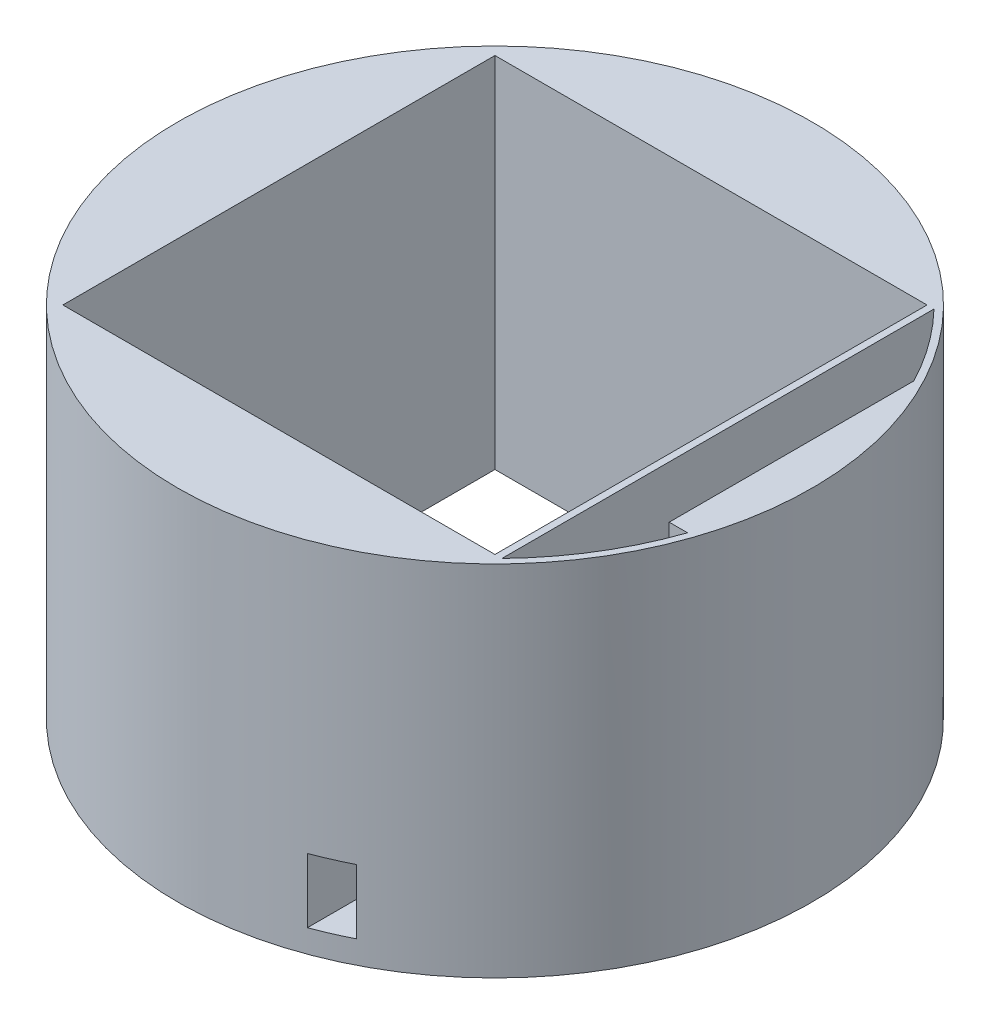
SolidWorks part; units mm, degrees
ref_plane "Front Plane" through (0, 0, 0) normal (0, 0, 1) x (1, 0, 0)
ref_plane "Top Plane" through (0, 0, 0) normal (0, 1, 0) x (1, 0, 0)
ref_plane "Right Plane" through (0, 0, 0) normal (1, 0, 0) x (0, 0, -1)
sketch "Sketch1" plane through (0, 0, 0) normal (0, 1, 0) x (1, 0, 0)
  line L0 (-23.5, -23.5) -> (-25.2587, -23.5)
  line L13 (-23.5, -23.5) -> (23.5, -23.5)
  line L14 (-23.5, -23.5) -> (-23.5, 23.5)
  line L15 (-23.5, 23.5) -> (23.5, 23.5)
  line L16 (23.5, -23.5) -> (23.5, 23.5)
  line L17 (-23.5, -23.5) -> (23.5, 23.5) construction
  line L18 (-23.5, 23.5) -> (23.5, -23.5) construction
  line L19 (-23.5, -10.9835) -> (-32.7049, -10.9835)
  line L20 (23.5, -23.5) -> (24.254, -23.5)
  line L21 (23.5, -10.9835) -> (31.9354, -10.9835)
  circle A3 centre (0, 0) radius 34.5
  arc A4 (24.254, -23.5) -> (31.9354, -10.9835) centre (0, 0) ccw
extrude "Boss-Extrude1" add sketch "Sketch1" along normal blind 2.5 contours A4 L20 L13 L19 A3 L0 L14 L15 L16 L21
sketch "Sketch2" plane through (0, 2.5, 0) normal (0, 1, 0) x (1, 0, 0)
  line L0 (23.5, -10.9835) -> (31.9354, -10.9835)
  line L1 (-23.5, -23.5) -> (11.9573, -23.5)
  line L2 (-23.5, -10.9835) -> (-23.5, 23.5)
  line L4 (23.5, -10.9835) -> (23.5, 23.5)
  line L5 (-23.5, -23.5) -> (23.5, 23.5) construction
  line L6 (-23.5, 23.5) -> (23.5, -23.5) construction
  line L7 (23.5, -23.5) -> (24.254, -23.5)
  line L8 (-23.5, -10.9835) -> (-32.7049, -10.9835)
  line L9 (-23.5, -23.5) -> (-25.2587, -23.5)
  line L10 (-25.2587, -23.5) -> (24.254, -23.5) construction
  line L14 (-23.5, 23.5) -> (23.5, 23.5)
  line L15 (15.6884, -23.5) -> (15.6884, -30.7266)
  line L16 (11.9573, -23.5) -> (11.9573, -32.3616)
  line L17 (15.6884, -23.5) -> (23.5, -23.5)
  arc A1 (24.254, -23.5) -> (31.9354, -10.9835) centre (0, 0) ccw
  arc A3 (15.6884, -30.7266) -> (11.9573, -32.3616) centre (0, 0) ccw
  arc M7 (31.9354, -10.9835) -> (24.254, -23.5) centre (0, 0) cw
  line M8 (24.254, -23.5) -> (-25.2587, -23.5)
  arc M9 (-25.2587, -23.5) -> (-32.7049, -10.9835) centre (0, 0) ccw
  line M10 (-32.7049, -10.9835) -> (-23.5, -10.9835)
  line M11 (-23.5, -10.9835) -> (-23.5, 23.5)
  line M12 (-23.5, 23.5) -> (23.5, 23.5)
  line M13 (23.5, 23.5) -> (23.5, -10.9835)
  line M14 (23.5, -10.9835) -> (31.9354, -10.9835)
extrude "Boss-Extrude2" add sketch "Sketch2" along normal blind 4.5 contours L15 M8 M9 M10 M11 M12 M13 M14 M7 | L16 M8 M9 | L4 L9 L1 L7 A1 L0 | L2 L8
sketch "Sketch3" plane through (0, 7, 0) normal (0, 1, 0) x (1, 0, 0)
  line L0 (24.254, -10.9835) -> (24.254, -23.5)
  line L1 (-23.5, -23.5) -> (11.9573, -23.5)
  line L2 (-23.5, -23.5) -> (-23.5, 23.5)
  line L4 (23.5, -23.5) -> (23.5, 23.5)
  line L5 (-23.5, -23.5) -> (23.5, 23.5) construction
  line L6 (-23.5, 23.5) -> (23.5, -23.5) construction
  line L7 (23.5, -10.9835) -> (31.9354, -10.9835) construction
  line L10 (29.8991, -10.9835) -> (31.9354, -10.9835)
  line L11 (29.8991, -10.9835) -> (24.254, -10.9835)
  line L12 (24.254, -23.5) -> (15.6884, -23.5) construction
  line L16 (11.9573, -23.5) -> (11.9573, -32.3616)
  line L17 (15.6884, -23.5) -> (15.6884, -30.7266)
  line L18 (15.6884, -23.5) -> (23.5, -23.5)
  line L19 (-23.5, 23.5) -> (23.5, 23.5)
  arc A2 (24.254, -23.5) -> (31.9354, -10.9835) centre (0, 0) ccw
  circle A5 centre (0, 0) radius 34.5
  arc M2 (15.6884, -30.7266) -> (-32.7049, -10.9835) centre (0, 0) ccw
  line M3 (23.5, -10.9835) -> (31.9354, -10.9835)
  arc M4 (31.9354, -10.9835) -> (24.254, -23.5) centre (0, 0) cw
  line M5 (24.254, -23.5) -> (15.6884, -23.5)
  line M6 (-23.5, -10.9835) -> (-23.5, 23.5)
  line M7 (-23.5, 23.5) -> (23.5, 23.5)
  line M8 (23.5, 23.5) -> (23.5, -10.9835)
  line M32 (15.6884, -23.5) -> (15.6884, -30.7266)
  line M33 (-32.7049, -10.9835) -> (-23.5, -10.9835)
extrude "Boss-Extrude3" add sketch "Sketch3" along normal blind 2.5 contours A5 L16 L1 L2 M33 | L4 L0 M5 M3 | M4 M5 M32 M2 M33 M6 M7 M8 M3
sketch "Sketch4" plane through (0, 9.5, 0) normal (0, 1, 0) x (1, 0, 0)
  line L0 (24.254, -23.5) -> (24.254, 23.5)
  line L1 (29.9354, -10.9835) -> (29.9354, 15.6326)
  line L2 (24.254, -10.9835) -> (31.9354, -10.9835) construction
  line L3 (29.9354, -10.9835) -> (31.9354, -10.9835)
  line L4 (-23.5, -23.5) -> (23.5, -23.5)
  line L5 (-23.5, -23.5) -> (-23.5, 23.5)
  line L6 (-23.5, 23.5) -> (23.5, 23.5)
  line L7 (23.5, -23.5) -> (23.5, 23.5)
  line L8 (-23.5, -23.5) -> (23.5, 23.5) construction
  line L9 (-23.5, 23.5) -> (23.5, -23.5) construction
  circle A0 centre (0, 0) radius 34.5
  arc A1 (29.9354, 15.6326) -> (24.254, 23.5) centre (0, 0) ccw
  arc A2 (29.9354, 15.6326) -> (24.254, 23.5) centre (0, 0) ccw
  arc A3 (24.254, -23.5) -> (31.9354, -10.9835) centre (0, 0) ccw
  line M1 (23.5, 23.5) -> (23.5, -23.5)
  line M2 (23.5, -23.5) -> (15.6884, -23.5)
  line M3 (15.6884, -23.5) -> (15.6884, -30.7266)
  arc M4 (15.6884, -30.7266) -> (11.9573, -32.3616) centre (0, 0) ccw
  line M5 (11.9573, -32.3616) -> (11.9573, -23.5)
  line M6 (11.9573, -23.5) -> (-23.5, -23.5)
  line M7 (-23.5, -23.5) -> (-23.5, 23.5)
  line M8 (-23.5, 23.5) -> (23.5, 23.5)
  arc M9 (31.9354, -10.9835) -> (24.254, -23.5) centre (0, 0) cw
  line M10 (24.254, -23.5) -> (24.254, -10.9835)
  line M11 (24.254, -10.9835) -> (31.9354, -10.9835)
extrude "Boss-Extrude4" add sketch "Sketch4" along normal blind 29.5 contours A1 L1 L0 M8 M1 M2 M3 M4 M5 M6 M7 M11 M9 M10 | A0 L4 M5 M3
